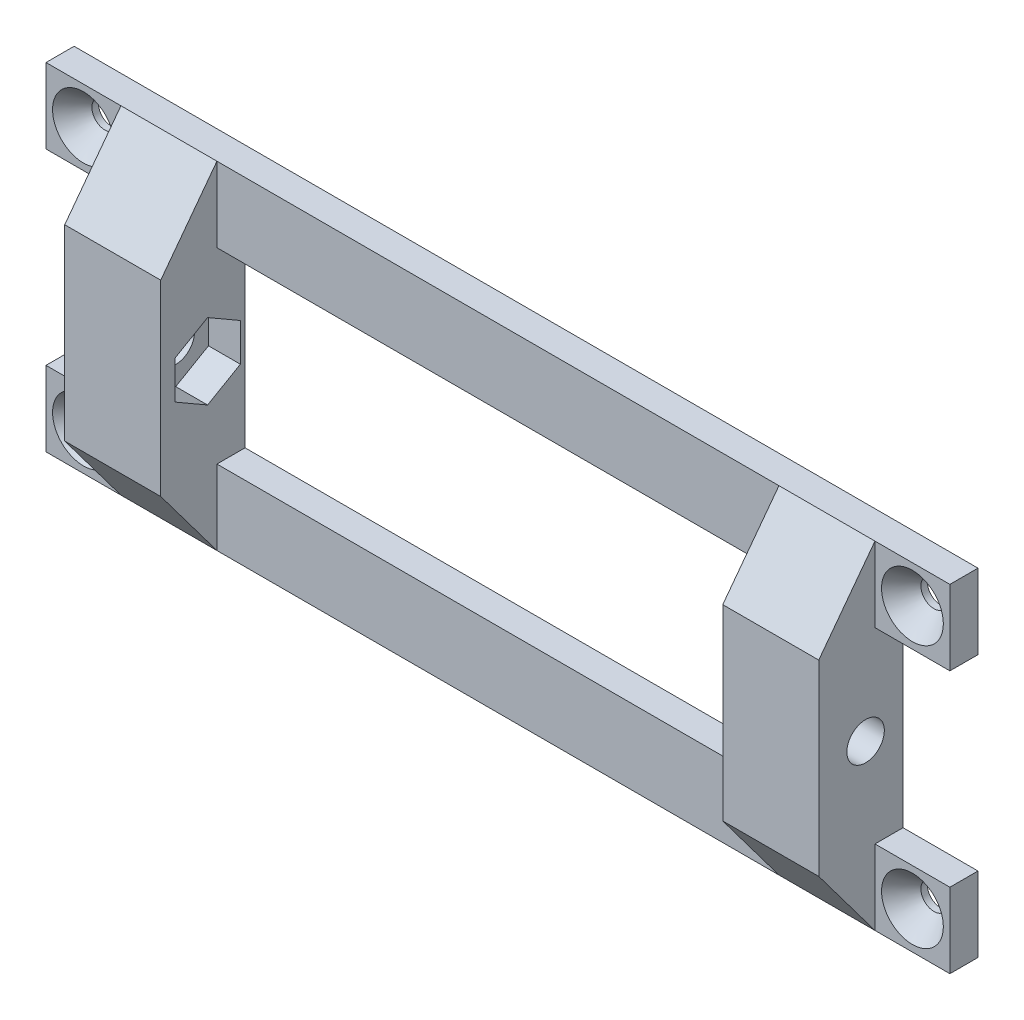
SolidWorks part; units mm, degrees
ref_plane "정면" through (0, 0, 0) normal (0, 0, 1) x (1, 0, 0)
ref_plane "윗면" through (0, 0, 0) normal (0, 1, 0) x (1, 0, 0)
ref_plane "우측면" through (0, 0, 0) normal (1, 0, 0) x (0, 0, -1)
sketch "스케치1" plane through (0, 0, 0) normal (0, 0, 1) x (1, 0, 0)
  line L0 (0, 0) -> (0, 18) construction
  line L1 (-48.25, 18) -> (48.25, 18)
  line L2 (-40.25, 10) -> (-40.25, -10)
  line L3 (-48.25, -18) -> (48.25, -18)
  line L4 (40.25, 10) -> (40.25, -10)
  line L6 (-30, -10) -> (30, -10)
  line L9 (-40.25, 10) -> (-48.25, 10)
  line L10 (-48.25, 18) -> (-48.25, 10)
  line L11 (0, 0) -> (-40.25, 0) construction
  line L12 (-40.25, -10) -> (-48.25, -10)
  line L13 (-48.25, -18) -> (-48.25, -10)
  line L16 (48.25, -18) -> (48.25, -10)
  line L17 (40.25, -10) -> (48.25, -10)
  line L18 (48.25, 18) -> (48.25, 10)
  line L19 (40.25, 10) -> (48.25, 10)
  line L20 (-30, -10) -> (-30, 10)
  line L21 (-30, 10) -> (30, 10)
  line L22 (30, -10) -> (30, 10)
  line L23 (-30, -10) -> (30, 10) construction
  line L24 (-30, 10) -> (30, -10) construction
  point P0 (0, 0)
  dimension "D1" = 96.5
  dimension "D2" = 36
  dimension "D3" = 8
  dimension "D4" = 8
  dimension "D5" = 60
extrude "보스-돌출1" add sketch "스케치1" along normal blind 3
sketch "스케치2" plane through (0, 0, 3) normal (0, 0, 1) x (1, 0, 0)
  line L1 (40.25, 10) -> (30, 10)
  line L2 (40.25, 10) -> (40.25, -10)
  line L3 (40.25, -10) -> (30, -10)
  line L4 (30, 10) -> (30, -10)
  line L5 (-40.25, 10) -> (-30, 10)
  line L6 (-40.25, 10) -> (-40.25, -10)
  line L7 (-40.25, -10) -> (-30, -10)
  line L8 (-30, 10) -> (-30, -10)
extrude "보스-돌출2" add sketch "스케치2" along normal blind 6 contours L2 L1 L4 L3 | L6 L5 L8 L7
sketch "스케치3" plane through (0, 0, 0) normal (1, 0, 0) x (0, 0, -1)
  line L0 (-4, 0) -> (0, 0) construction
  circle A0 centre (-4, 0) radius 2
  dimension "D1" = 4
  dimension "D2" = 4
extrude "컷-돌출1" cut sketch "스케치3" against normal through all both and the other way through all
sketch "스케치4" plane through (0, 0, 0) normal (0, 0, 1) x (1, 0, 0)
  line L0 (0, 0) -> (0, 18) construction
  line L1 (48.25, 18) -> (-48.25, 18) construction
  line L2 (0, 0) -> (40.25, 0) construction
  line L3 (40.25, 10) -> (40.25, -10) construction
  line L4 (40.25, 0) -> (0, 0) construction
  line L5 (40.25, 10) -> (48.25, 18) construction
  circle A0 centre (44.25, 14) radius 1.4
  circle A1 centre (-44.25, 14) radius 1.4
  circle A2 centre (44.25, -14) radius 1.4
  circle A3 centre (-44.25, -14) radius 1.4
  dimension "D1" = 2.8
extrude "컷-돌출2" cut sketch "스케치4" along normal through all
sketch "스케치5" plane through (40.25, 0, 0) normal (1, 0, 0) x (0, 0, -1)
  line L0 (-9, 10) -> (-3, 18)
  line L1 (-3, 18) -> (-3, 10)
  line L2 (-3, 10) -> (-9, 10)
  line L3 (-9, -10) -> (-3, -10)
  line L4 (-3, -10) -> (-3, -18)
  line L5 (-3, -18) -> (-9, -10)
extrude "보스-돌출3" add sketch "스케치5" against normal up to surface (10.25 mm away) up to face at (30, 0, 6)
sketch "스케치6" plane through (-40.25, 0, 0) normal (-1, 0, 0) x (0, 0, 1)
  line L0 (3, 18) -> (3, 10)
  line L1 (3, 10) -> (9, 10)
  line L2 (9, 10) -> (3, 18)
  line L3 (3, -10) -> (3, -18)
  line L4 (3, -18) -> (9, -10)
  line L5 (9, -10) -> (3, -10)
extrude "보스-돌출4" add sketch "스케치6" against normal up to surface (10.25 mm away) up to face at (-30, 0, 2)
sketch "스케치7" plane through (30, 0, 0) normal (-1, 0, 0) x (0, 0, 1)
  line L1 (4, 4.0415) -> (0.5, 2.0207)
  line L2 (0.5, 2.0207) -> (0.5, -2.0207)
  line L3 (0.5, -2.0207) -> (4, -4.0415)
  line L4 (4, -4.0415) -> (7.5, -2.0207)
  line L5 (7.5, -2.0207) -> (7.5, 2.0207)
  line L6 (7.5, 2.0207) -> (4, 4.0415)
  circle A0 centre (4, 0) radius 3.5 construction
  dimension "D1" = 7
extrude "컷-돌출3" cut sketch "스케치7" against normal blind 3.4
mirror "대칭 복사2" about plane through (0, 0, 0) normal (1, 0, 0) of "컷-돌출3"
chamfer "모따기1" distance 1.9 distance2 2.3 4 edges at (42.85, 14, 3) (-45.65, 14, 3) (-45.65, -14, 3) (42.85, -14, 3)
